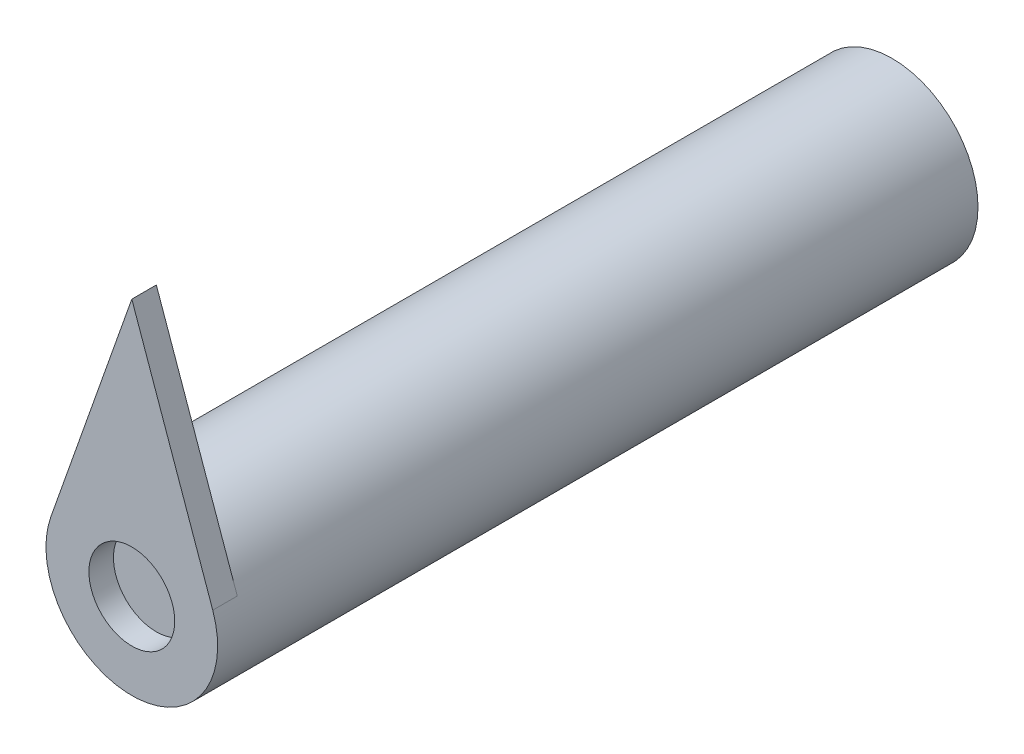
SolidWorks part; units mm, degrees
ref_plane "Front Plane" through (0, 0, 0) normal (0, 0, 1) x (1, 0, 0)
ref_plane "Top Plane" through (0, 0, 0) normal (0, 1, 0) x (1, 0, 0)
ref_plane "Right Plane" through (0, 0, 0) normal (1, 0, 0) x (0, 0, -1)
sketch "Sketch1" plane through (0, 0, 0) normal (0, 0, 1) x (1, 0, 0)
  circle A0 centre (0, 0) radius 3.5
  dimension "D1" = 7
extrude "Boss-Extrude1" add sketch "Sketch1" along normal blind 30
sketch "Sketch3" plane through (0, 0, 30) normal (0, 0, 1) x (1, 0, 0)
  line L0 (0, 10.5) -> (-3.2998, 1.1667)
  line L1 (0, 10.5) -> (3.2998, 1.1667)
  circle A0 centre (0, 0) radius 1.75
  arc A1 (-3.2998, 1.1667) -> (3.2998, 1.1667) centre (0, 0) ccw
  dimension "D1" = 3.5
  dimension "D2" = 7
  dimension "D3" = 10.5
extrude "Boss-Extrude2" add sketch "Sketch3" along normal blind 1
